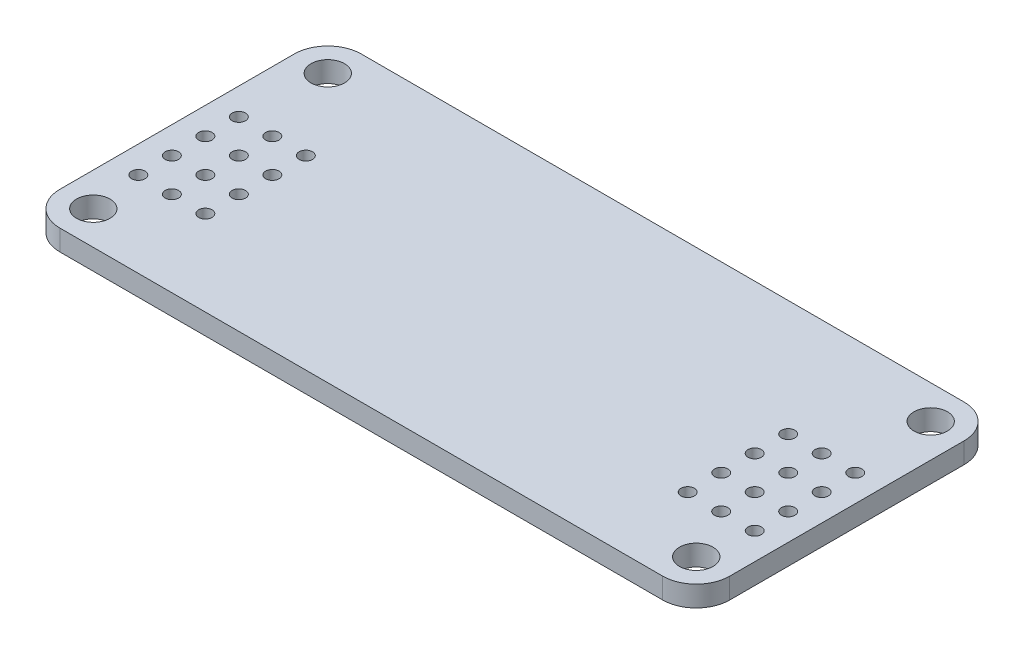
SolidWorks part; units mm, degrees
ref_plane "Front Plane" through (0, 0, 0) normal (0, 0, 1) x (1, 0, 0)
ref_plane "Top Plane" through (0, 0, 0) normal (0, 1, 0) x (1, 0, 0)
ref_plane "Right Plane" through (0, 0, 0) normal (1, 0, 0) x (0, 0, -1)
sketch "Sketch1" plane through (0, 0, 0) normal (0, 1, 0) x (1, 0, 0)
  line L1 (-25.4, -11.43) -> (25.4, -11.43)
  line L2 (-25.4, -11.43) -> (-25.4, 11.43)
  line L3 (-25.4, 11.43) -> (25.4, 11.43)
  line L4 (25.4, -11.43) -> (25.4, 11.43)
  line L5 (-25.4, -11.43) -> (25.4, 11.43) construction
  line L6 (-25.4, 11.43) -> (25.4, -11.43) construction
  point P0 (0, 0)
  dimension "D1" = 22.86
  dimension "D2" = 50.8
extrude "Boss-Extrude1" add sketch "Sketch1" along normal blind 1.57
sketch "Sketch2" plane through (0, 1.57, 0) normal (0, 1, 0) x (1, 0, 0)
  line L1 (-22.86, -8.89) -> (22.86, -8.89)
  line L2 (-22.86, -8.89) -> (-22.86, 8.89)
  line L3 (-22.86, 8.89) -> (22.86, 8.89)
  line L4 (22.86, -8.89) -> (22.86, 8.89)
  line L5 (-22.86, -8.89) -> (22.86, 8.89) construction
  line L6 (-22.86, 8.89) -> (22.86, -8.89) construction
  point P0 (0, 0)
  dimension "D1" = 17.78
  dimension "D2" = 45.72
hole_wizard "1/16 (0.1) Dowel Hole1" positions "Sketch3" profile "Sketch4" hole size "1/16" standard "ANSI Inch" end condition through all
sketch "Sketch3" plane through (0, 1.57, 0) normal (0, 1, 0) x (1, 0, 0)
  point P0 (-22.86, 8.89)
  point P3 (22.86, 8.89)
  point P6 (22.86, -8.89)
  point P9 (-22.86, -8.89)
sketch "Sketch4" plane through (-22.86, 1.57, -8.89) normal (1, 0, 0) x (0, 0, 1)
  line L0 (0, 0) -> (0, 1.57)
  line L1 (0, 1.57) -> (1.27, 1.57)
  line L2 (1.27, 1.57) -> (1.27, 0)
  line L5 (1.27, 0) -> (0, 0)
  line L11 (0, -6.35) -> (0, 107.95) construction
  dimension "Thru Hole Dia." = 2.54
  dimension "Thru Hole Depth" = 1.57
fillet "Fillet1" radius 2.54 4 edges at (25.4, 0.785, -11.43) (25.4, 0.785, 11.43) (-25.4, 0.785, 11.43) (-25.4, 0.785, -11.43)
sketch "Sketch5" plane through (0, 1.57, 0) normal (0, 1, 0) x (1, 0, 0)
  line L0 (-25.4, 0) -> (25.4, 0) construction
  line L1 (-25.4, 8.89) -> (-25.4, -8.89) construction
  line L2 (25.4, -8.89) -> (25.4, 8.89) construction
  line L3 (-20.828, 11.43) -> (-20.828, -11.43) construction
  line L4 (22.86, 11.43) -> (-22.86, 11.43) construction
  line L5 (-22.86, -11.43) -> (22.86, -11.43) construction
  line L6 (-20.828, 0) -> (-20.828, -2.54)
  line L7 (0, 11.43) -> (0, -11.43) construction
  line L8 (20.828, 0) -> (20.828, -2.54)
  line L9 (-20.828, -2.54) -> (-20.828, -4.9654)
  line L10 (20.828, -2.54) -> (20.828, -4.9654)
  point P12 (-20.828, 0)
  point P16 (-20.828, 0)
  point P21 (-20.828, -1.27)
  dimension "D1" = 4.572
  dimension "D2" = 10.16
  dimension "D3" = 2.54
  dimension "D4" = 2.4254
hole_wizard "1/16 (0.04) Dowel Hole3" positions "Sketch10" profile "Sketch11" hole size "1/16" standard "ANSI Inch" end condition through all
sketch "Sketch10" plane through (0, 1.57, 0) normal (0, 1, 0) x (1, 0, 0)
  point P0 (-20.828, -4.9654)
sketch "Sketch11" plane through (-20.828, 1.57, 4.9654) normal (1, 0, 0) x (0, 0, 1)
  line L0 (0, 0) -> (0, 1.57)
  line L1 (0, 1.57) -> (0.508, 1.57)
  line L2 (0.508, 1.57) -> (0.508, 0)
  line L5 (0.508, 0) -> (0, 0)
  line L11 (0, -6.35) -> (0, 107.95) construction
  dimension "Thru Hole Dia." = 1.016
  dimension "Thru Hole Depth" = 1.57
pattern_linear "LPattern6" count 4 spacing 2.54 along (0, 0, -1) count 2 spacing 2.54 along (-1, 0, 0) of "1/16 (0.04) Dowel Hole3"
pattern_linear "LPattern7" count 2 spacing 2.54 along (1, 0, 0) count 4 spacing 2.54 along (0, 0, -1) of "1/16 (0.04) Dowel Hole3"
pattern_linear "LPattern8" count 2 spacing 41.656 along (1, 0, 0) of "LPattern6", "LPattern7", "1/16 (0.04) Dowel Hole3"
